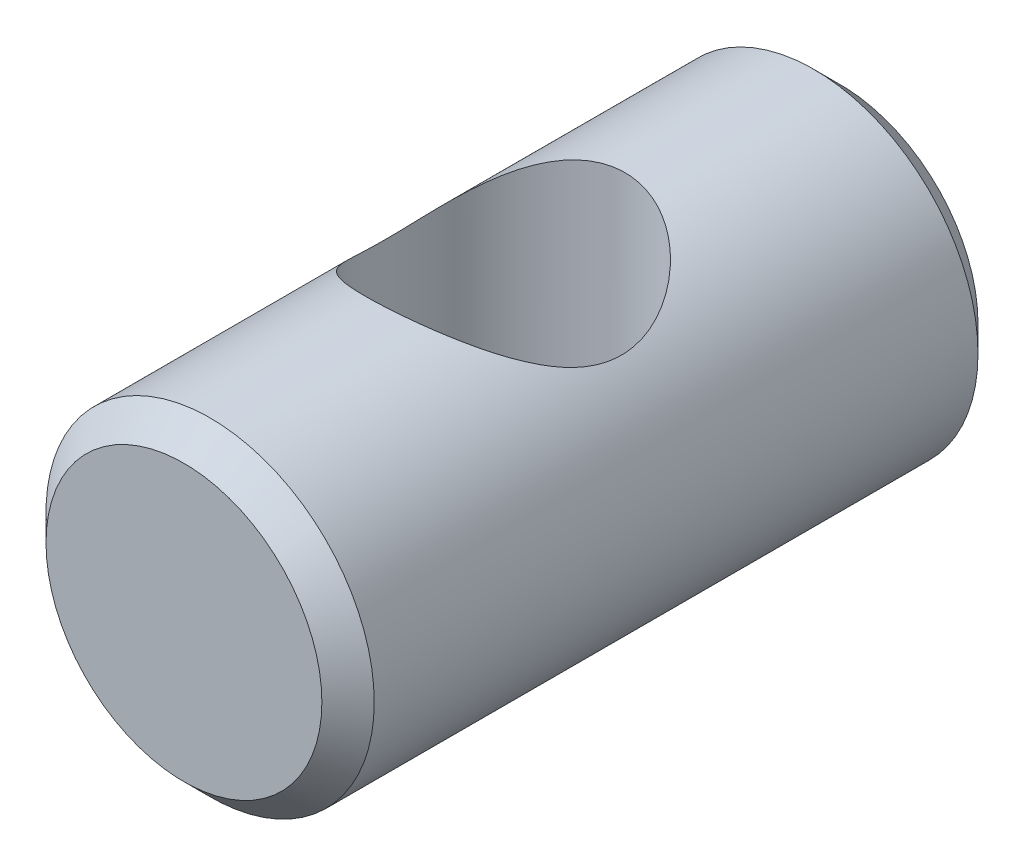
SolidWorks part; units mm, degrees
ref_plane "Front Plane" through (0, 0, 0) normal (0, 0, 1) x (1, 0, 0)
ref_plane "Top Plane" through (0, 0, 0) normal (0, 1, 0) x (1, 0, 0)
ref_plane "Right Plane" through (0, 0, 0) normal (1, 0, 0) x (0, 0, -1)
sketch "Sketch1" plane through (0, 0, 0) normal (0, 0, 1) x (1, 0, 0)
  circle A0 centre (0, 0) radius 4.765
  dimension "D1" = 9.53
extrude "Boss-Extrude1" add sketch "Sketch1" along normal mid plane 19.05
chamfer "Chamfer1" distance 0.76 angle 45 1 edges at (4.765, 0, 9.525)
chamfer "Chamfer2" distance 0.76 angle 45 1 edges at (4.765, 0, -9.525)
sketch "Sketch2" plane through (0, 0, 0) normal (0, 1, 0) x (1, 0, 0)
  circle A0 centre (-0.25, 0) radius 3.43
  dimension "D1" = 6.86
  dimension "D2" = 0.25
extrude "Cut-Extrude1" cut sketch "Sketch2" against normal mid plane 19.05 contours A0
